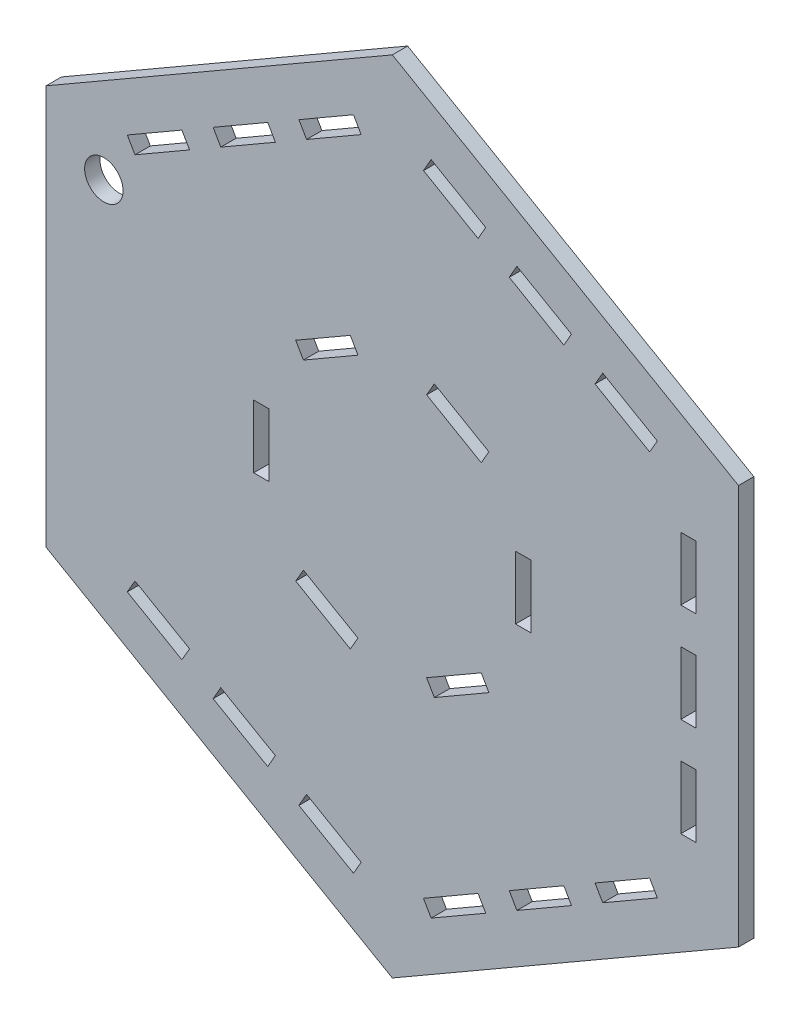
SolidWorks part; units mm, degrees
ref_plane "Alzado" through (0, 0, 0) normal (0, 0, 1) x (1, 0, 0)
ref_plane "Planta" through (0, 0, 0) normal (0, 1, 0) x (1, 0, 0)
ref_plane "Vista lateral" through (0, 0, 0) normal (1, 0, 0) x (0, 0, -1)
sketch "Croquis1" plane through (0, 0, 0) normal (0, 0, 1) x (1, 0, 0)
  line L0 (-46.0585, -1.7557) -> (-46.8085, -3.0548) construction
  line L1 (-51.3845, 1.3193) -> (-52.8845, -1.2788)
  line L2 (-51.3845, 1.3193) -> (-40.7324, -4.8307)
  line L3 (-52.8845, -1.2788) -> (-42.2324, -7.4288)
  line L4 (-40.7324, -4.8307) -> (-42.2324, -7.4288)
  line L5 (-58.0832, 32.9568) -> (-58.0832, 5.1868) construction
  line L6 (-58.0832, 5.1868) -> (-34.0337, -8.6982) construction
  line L7 (-34.0337, -8.6982) -> (-9.9842, 5.1868) construction
  line L8 (-9.9842, 5.1868) -> (-9.9842, 32.9568) construction
  line L9 (-9.9842, 32.9568) -> (-34.0337, 46.8418) construction
  line L10 (-34.0337, 46.8418) -> (-58.0832, 32.9568) construction
  line L11 (-58.0832, 32.9568) -> (-9.9842, 5.1868) construction
  line L12 (-22.6238, 77.4843) -> (-20.6802, 80.8508) construction
  line L13 (-26.4612, 83.1639) -> (-27.9499, 80.5593)
  line L14 (-27.9499, 80.5593) -> (-17.2977, 74.4093)
  line L15 (-17.2977, 74.4093) -> (-15.809, 77.0139)
  line L16 (-15.809, 77.0139) -> (-26.4612, 83.1639)
  line L17 (7.0333, 63.8258) -> (17.6854, 57.6758)
  line L18 (5.522, 61.2343) -> (7.0333, 63.8258)
  line L19 (16.1741, 55.0843) -> (5.522, 61.2343)
  line L20 (17.6854, 57.6758) -> (16.1741, 55.0843)
  line L21 (5.522, -23.0907) -> (7.0333, -25.6823)
  line L22 (-34.0337, 97.0718) -> (-101.5837, 58.0718)
  line L23 (-101.5837, 58.0718) -> (-101.5837, -19.9282)
  line L24 (-101.5837, -19.9282) -> (-34.0337, -58.9282)
  line L25 (-34.0337, -58.9282) -> (33.5163, -19.9282)
  line L26 (33.5163, -19.9282) -> (33.5163, 58.0718)
  line L27 (33.5163, 58.0718) -> (-34.0337, 97.0718)
  line L28 (-34.0337, 84.0718) -> (-90.3253, 51.5718) construction
  line L29 (-90.3253, 51.5718) -> (-90.3253, -13.4282) construction
  line L30 (-90.3253, -13.4282) -> (-34.0337, -45.9282) construction
  line L31 (-34.0337, -45.9282) -> (22.258, -13.4282) construction
  line L32 (22.258, -13.4282) -> (22.258, 51.5718) construction
  line L33 (22.258, 51.5718) -> (-34.0337, 84.0718) construction
  line L34 (-34.0337, 97.0718) -> (-34.0337, 84.0718) construction
  line L35 (22.258, 51.5718) -> (33.5163, 58.0718)
  line L36 (-9.7253, 73.5014) -> (-11.2139, 70.8968)
  line L37 (-11.2139, 70.8968) -> (-0.5618, 64.7468)
  line L38 (-0.5618, 64.7468) -> (0.9269, 67.3514)
  line L39 (0.9269, 67.3514) -> (-9.7253, 73.5014)
  line L40 (16.1741, -16.9407) -> (5.522, -23.0907)
  line L41 (17.6854, -19.5323) -> (16.1741, -16.9407)
  line L42 (7.0333, -25.6823) -> (17.6854, -19.5323)
  line L43 (0.9269, -29.2078) -> (-9.7253, -35.3578)
  line L44 (-0.5618, -26.6032) -> (0.9269, -29.2078)
  line L45 (-11.2139, -32.7532) -> (-0.5618, -26.6032)
  line L46 (-9.7253, -35.3578) -> (-11.2139, -32.7532)
  line L47 (-15.809, -38.8703) -> (-26.4612, -45.0203)
  line L48 (-17.2977, -36.2657) -> (-15.809, -38.8703)
  line L49 (-27.9499, -42.4157) -> (-17.2977, -36.2657)
  line L50 (-26.4612, -45.0203) -> (-27.9499, -42.4157)
  line L51 (-50.7697, -36.2657) -> (-52.2583, -38.8703)
  line L52 (-40.1175, -42.4157) -> (-50.7697, -36.2657)
  line L53 (-41.6062, -45.0203) -> (-40.1175, -42.4157)
  line L54 (-52.2583, -38.8703) -> (-41.6062, -45.0203)
  line L55 (-67.5056, -26.6032) -> (-68.9943, -29.2078)
  line L56 (-56.8534, -32.7532) -> (-67.5056, -26.6032)
  line L57 (-58.3421, -35.3578) -> (-56.8534, -32.7532)
  line L58 (-68.9943, -29.2078) -> (-58.3421, -35.3578)
  line L59 (-84.2415, -16.9407) -> (-73.5894, -23.0907)
  line L60 (-85.7528, -19.5323) -> (-84.2415, -16.9407)
  line L61 (-75.1007, -25.6823) -> (-85.7528, -19.5323)
  line L62 (-73.5894, -23.0907) -> (-75.1007, -25.6823)
  line L63 (-73.5894, 61.2343) -> (-75.1007, 63.8258)
  line L64 (-84.2415, 55.0843) -> (-73.5894, 61.2343)
  line L65 (-85.7528, 57.6758) -> (-84.2415, 55.0843)
  line L66 (-75.1007, 63.8258) -> (-85.7528, 57.6758)
  line L67 (-68.9943, 67.3514) -> (-58.3421, 73.5014)
  line L68 (-67.5056, 64.7468) -> (-68.9943, 67.3514)
  line L69 (-56.8534, 70.8968) -> (-67.5056, 64.7468)
  line L70 (-58.3421, 73.5014) -> (-56.8534, 70.8968)
  line L71 (-52.2583, 77.0139) -> (-41.6062, 83.1639)
  line L72 (-50.7697, 74.4093) -> (-52.2583, 77.0139)
  line L73 (-40.1175, 80.5593) -> (-50.7697, 74.4093)
  line L74 (-41.6062, 83.1639) -> (-40.1175, 80.5593)
  line L75 (22.258, 44.5468) -> (25.258, 44.5468)
  line L76 (22.258, 25.2218) -> (25.258, 25.2218)
  line L77 (22.258, 25.2218) -> (22.258, 12.9218)
  line L78 (22.258, 12.9218) -> (25.258, 12.9218)
  line L79 (25.258, 25.2218) -> (25.258, 12.9218)
  line L80 (22.258, 25.2218) -> (25.258, 12.9218) construction
  line L81 (22.258, 12.9218) -> (25.258, 25.2218) construction
  line L82 (22.258, 44.5468) -> (22.258, 32.2468)
  line L83 (22.258, 32.2468) -> (25.258, 32.2468)
  line L84 (25.258, 44.5468) -> (25.258, 32.2468)
  line L85 (22.258, 38.3968) -> (42.0199, 38.3968) construction
  line L86 (22.258, -6.4032) -> (22.258, 5.8968)
  line L87 (22.258, 5.8968) -> (25.258, 5.8968)
  line L88 (25.258, -6.4032) -> (25.258, 5.8968)
  line L89 (22.258, -6.4032) -> (25.258, -6.4032)
  line L90 (-25.835, 45.5724) -> (-15.1829, 39.4224)
  line L91 (-16.6829, 36.8243) -> (-15.1829, 39.4224)
  line L92 (-27.335, 42.9743) -> (-16.6829, 36.8243)
  line L93 (-27.335, 42.9743) -> (-25.835, 45.5724)
  line L94 (-58.0832, 19.0718) -> (-9.9842, 19.0718) construction
  line L95 (-52.8845, 39.4224) -> (-42.2324, 45.5724)
  line L96 (-40.7324, 42.9743) -> (-42.2324, 45.5724)
  line L97 (-51.3845, 36.8243) -> (-40.7324, 42.9743)
  line L98 (-51.3845, 36.8243) -> (-52.8845, 39.4224)
  line L99 (-27.335, -4.8307) -> (-25.835, -7.4288)
  line L100 (-27.335, -4.8307) -> (-16.6829, 1.3193)
  line L101 (-16.6829, 1.3193) -> (-15.1829, -1.2788)
  line L102 (-25.835, -7.4288) -> (-15.1829, -1.2788)
  line L103 (-9.9842, 25.2218) -> (-6.9842, 25.2218)
  line L104 (-9.9842, 25.2218) -> (-9.9842, 12.9218)
  line L105 (-9.9842, 12.9218) -> (-6.9842, 12.9218)
  line L106 (-6.9842, 25.2218) -> (-6.9842, 12.9218)
  line L107 (-34.0337, 22.9829) -> (-34.0337, 13.9163) construction
  line L108 (-58.0832, 25.2218) -> (-58.0832, 12.9218)
  line L109 (-58.0832, 12.9218) -> (-61.0832, 12.9218)
  line L110 (-61.0832, 25.2218) -> (-61.0832, 12.9218)
  line L111 (-58.0832, 25.2218) -> (-61.0832, 25.2218)
  circle A0 centre (-34.0337, 19.0718) radius 24.0495 construction
  circle A1 centre (-90.3253, 47.8218) radius 3.75
  circle A2 centre (-34.0337, 19.0718) radius 67.55 construction
  circle A3 centre (-34.0337, 19.0718) radius 56.2917 construction
  point P102 (23.758, 19.0718)
  dimension "D15" = 7.5
  dimension "D1" = 12.2999
  dimension "D2" = 0
  dimension "D3" = 78
  dimension "D4" = 26.35
  dimension "D5" = 26.35
  dimension "D6" = 6.15
  dimension "D7" = 13.175
  dimension "D8" = 0
  dimension "D9" = 12.3
  dimension "D10" = 3
  dimension "D11" = 0
  dimension "D12" = 0
  dimension "D13" = 12.3
  dimension "D14" = 13.175
  dimension "D16" = 1.5
  dimension "D17" = 3
  dimension "D18" = 12.3
  dimension "D19" = 6.15
  dimension "D20" = 6.15
  dimension "D21" = 6.15
  dimension "D22" = 0
  dimension "D23" = 3
extrude "Saliente-Extruir1" add sketch "Croquis1" along normal blind 3
